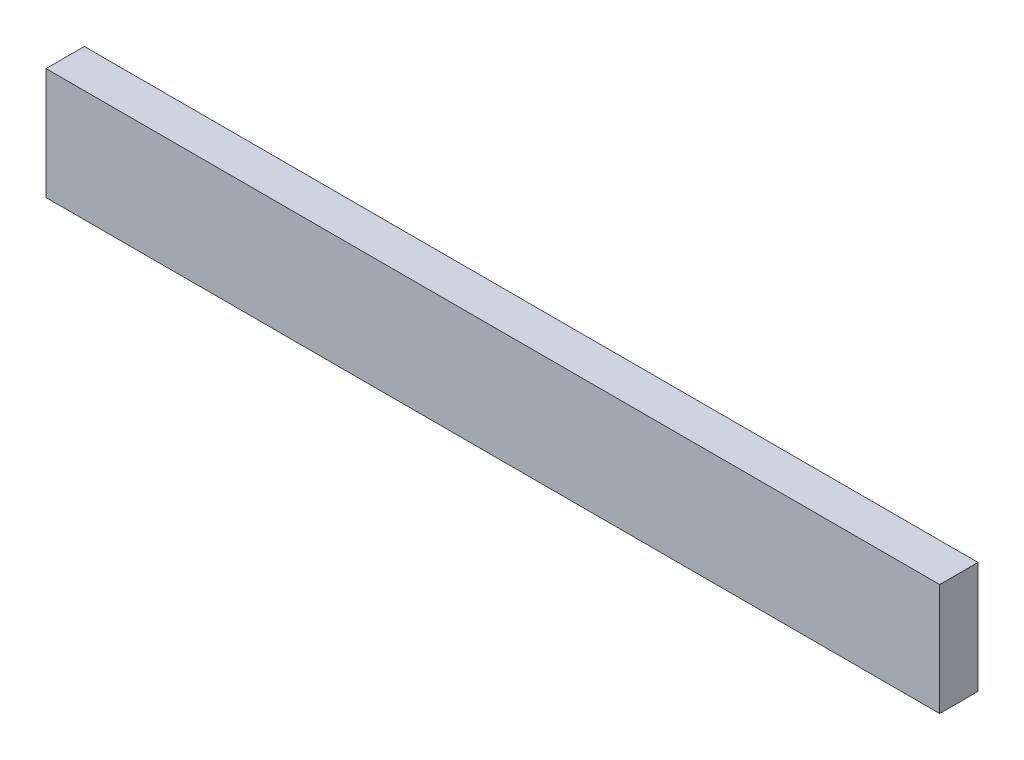
SolidWorks part; units mm, degrees
ref_plane "前视基准面" through (0, 0, 0) normal (0, 0, 1) x (1, 0, 0)
ref_plane "上视基准面" through (0, 0, 0) normal (0, 1, 0) x (1, 0, 0)
ref_plane "右视基准面" through (0, 0, 0) normal (1, 0, 0) x (0, 0, -1)
other "Configuration Table"
sketch "草图1" plane through (0, 0, 0) normal (0, 0, 1) x (1, 0, 0)
  line L1 (-140, -17.5) -> (140, -17.5)
  line L2 (-140, -17.5) -> (-140, 17.5)
  line L3 (-140, 17.5) -> (140, 17.5)
  line L4 (140, -17.5) -> (140, 17.5)
  line L5 (-140, -17.5) -> (140, 17.5) construction
  line L6 (-140, 17.5) -> (140, -17.5) construction
  point P0 (0, 0)
extrude "凸台-拉伸1" add sketch "草图1" along normal blind 12
